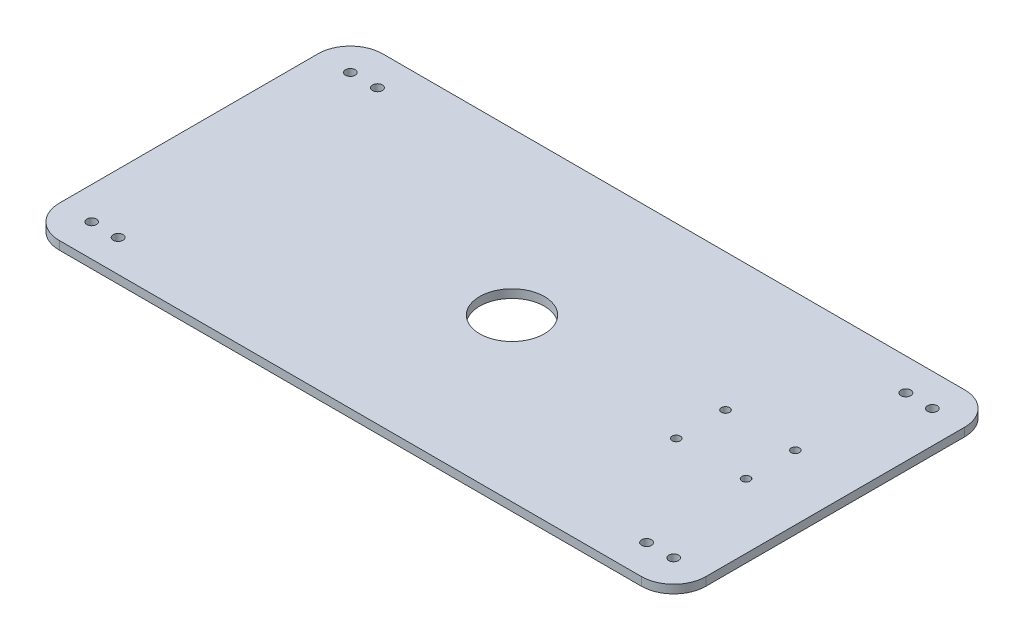
SolidWorks part; units mm, degrees
ref_plane "Front Plane" through (0, 0, 0) normal (0, 0, 1) x (1, 0, 0)
ref_plane "Top Plane" through (0, 0, 0) normal (0, 1, 0) x (1, 0, 0)
ref_plane "Right Plane" through (0, 0, 0) normal (1, 0, 0) x (0, 0, -1)
sketch "Sketch1" plane through (0, 0, 0) normal (0, 1, 0) x (1, 0, 0)
  line L1 (0, 0) -> (200, 0)
  line L2 (0, 0) -> (0, -100)
  line L3 (0, -100) -> (200, -100)
  line L4 (200, 0) -> (200, -100)
  dimension "D1" = 100
  dimension "D2" = 200
extrude "Boss-Extrude1" add sketch "Sketch1" along normal blind 2.6 contours L1 L4 L3 L2
fillet "Fillet1" radius 10 4 edges at (0, 1.3, 0) (0, 1.3, 100) (200, 1.3, 100) (200, 1.3, 0)
sketch "Sketch6" plane through (0, 0, 0) normal (0, -1, 0) x (1, 0, 0)
  line L0 (200, 10) -> (200, 90) construction
  line L1 (10, 0) -> (190, 0) construction
  circle A0 centre (190, 10) radius 1.5
  dimension "D1" = 3
  dimension "D2" = 10
  dimension "D3" = 10
ref_plane "Plane1" through (100, 0, 0) normal (1, 0, 0) x (0, 0, -1)
extrude "Cut-Extrude6" cut sketch "Sketch6" against normal blind 2.6 contours A0
ref_plane "Plane14" through (0, 0, 50) normal (0, 0, 1) x (1, 0, 0)
mirror "Mirror5" about plane through (100, 0, 0) normal (1, 0, 0) of "Cut-Extrude6"
mirror "Mirror6" about plane through (0, 0, 50) normal (0, 0, 1) of "Mirror5", "Cut-Extrude6"
sketch "Sketch15" plane through (0, 0, 0) normal (0, -1, 0) x (1, 0, 0)
  line L0 (100, 0) -> (100, 100) construction
  line L2 (0, 50) -> (200, 50) construction
  line L4 (0, 10) -> (0, 90) construction
  line L5 (200, 10) -> (200, 90) construction
  line L6 (10, 0) -> (190, 0) construction
  line L7 (10, 100) -> (190, 100) construction
  circle A0 centre (100, 50) radius 10
  dimension "D1" = 20
extrude "Cut-Extrude14" cut sketch "Sketch15" against normal through all contours A0
sketch "Sketch20" plane through (0, 2.6, 0) normal (0, 1, 0) x (1, 0, 0)
  line L0 (-1.43, -50) -> (1.43, -50) construction
  line L1 (158.41, -42.38) -> (158.41, 0) construction
  line L2 (10, 0) -> (190, 0) construction
  line L3 (158.41, 0) -> (158.41, -100) construction
  line L4 (10, -100) -> (190, -100) construction
  line L5 (180, -42.38) -> (180, 0) construction
  line L6 (180, 0) -> (180, -101.354) construction
  line L7 (200, -10) -> (200, -90) construction
  circle A0 centre (158.41, -42.38) radius 1.27
  circle A1 centre (180, -42.38) radius 1.27
  circle A2 centre (158.41, -57.62) radius 1.27
  circle A3 centre (180, -57.62) radius 1.27
  dimension "D1" = 7.62
  dimension "D2" = 7.62
  dimension "D4" = 7.62
  dimension "D7" = 2.54
  dimension "D8" = 2.54
  dimension "D9" = 2.54
  dimension "D10" = 2.54
  dimension "D3" = 21.59
  dimension "D5" = 7.62
  dimension "D6" = 20
extrude "Cut-Extrude15" cut sketch "Sketch20" against normal through all
sketch "Sketch23" plane through (0, 2.6, 0) normal (0, 1, 0) x (1, 0, 0)
  circle A0 centre (18.288, -9.906) radius 1.524
extrude "Cut-Extrude16" cut sketch "Sketch23" against normal blind 2.6
mirror "Mirror7" about plane through (100, 0, 0) normal (1, 0, 0) of "Cut-Extrude16"
mirror "Mirror8" about plane through (0, 0, 50) normal (0, 0, 1) of "Mirror7", "Cut-Extrude16"
